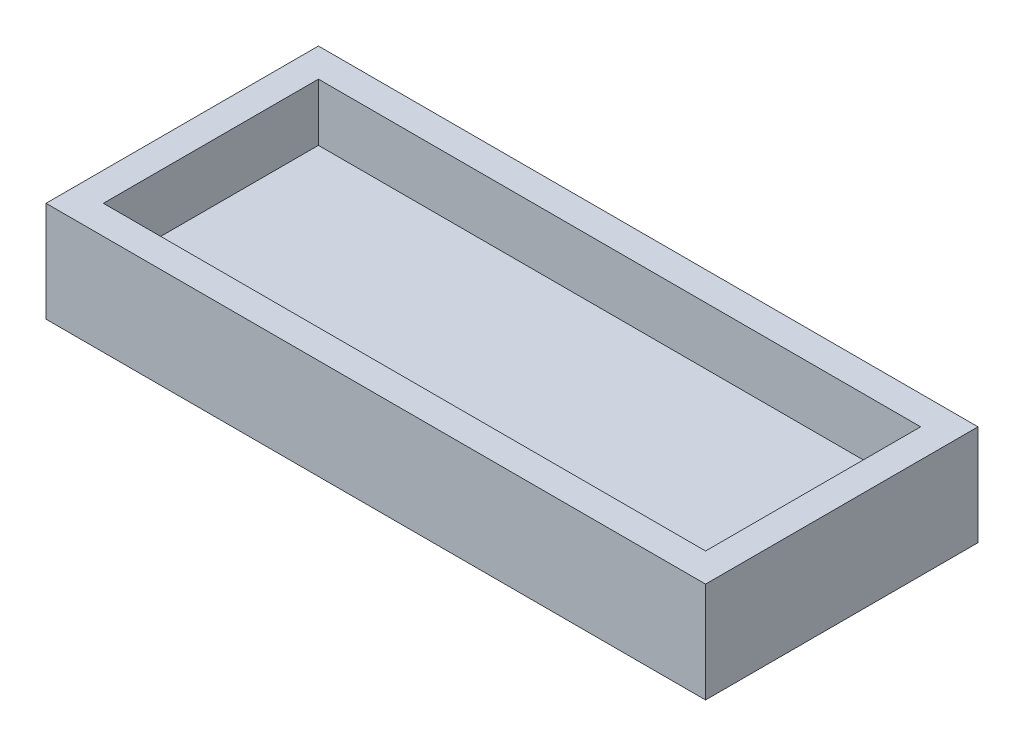
SolidWorks part; units mm, degrees
ref_plane "Front Plane" through (0, 0, 0) normal (0, 0, 1) x (1, 0, 0)
ref_plane "Top Plane" through (0, 0, 0) normal (0, 1, 0) x (1, 0, 0)
ref_plane "Right Plane" through (0, 0, 0) normal (1, 0, 0) x (0, 0, -1)
sketch "Sketch1" plane through (0, 0, 0) normal (0, 1, 0) x (1, 0, 0)
  line L1 (-21, 7.5) -> (21, 7.5)
  line L2 (-21, 7.5) -> (-21, -7.5)
  line L3 (-21, -7.5) -> (21, -7.5)
  line L4 (21, 7.5) -> (21, -7.5)
  line L5 (-21, 7.5) -> (21, -7.5) construction
  line L6 (-21, -7.5) -> (21, 7.5) construction
  point P0 (0, 0)
  dimension "D1" = 42
  dimension "D2" = 15
extrude "Boss-Extrude1" add sketch "Sketch1" along normal blind 3
sketch "Sketch2" plane through (0, 0, 0) normal (0, -1, 0) x (1, 0, 0)
  line L0 (23, 9.5) -> (23, -9.5)
  line L1 (21, 7.5) -> (-21, 7.5)
  line L2 (21, 7.5) -> (21, -7.5)
  line L3 (21, -7.5) -> (-21, -7.5)
  line L4 (-21, 7.5) -> (-21, -7.5)
  line L5 (23, -9.5) -> (-23, -9.5)
  line L6 (-23, 9.5) -> (-23, -9.5)
  line L7 (23, 9.5) -> (-23, 9.5)
  dimension "D1" = 2
extrude "Boss-Extrude2" add sketch "Sketch2" against normal blind 7
